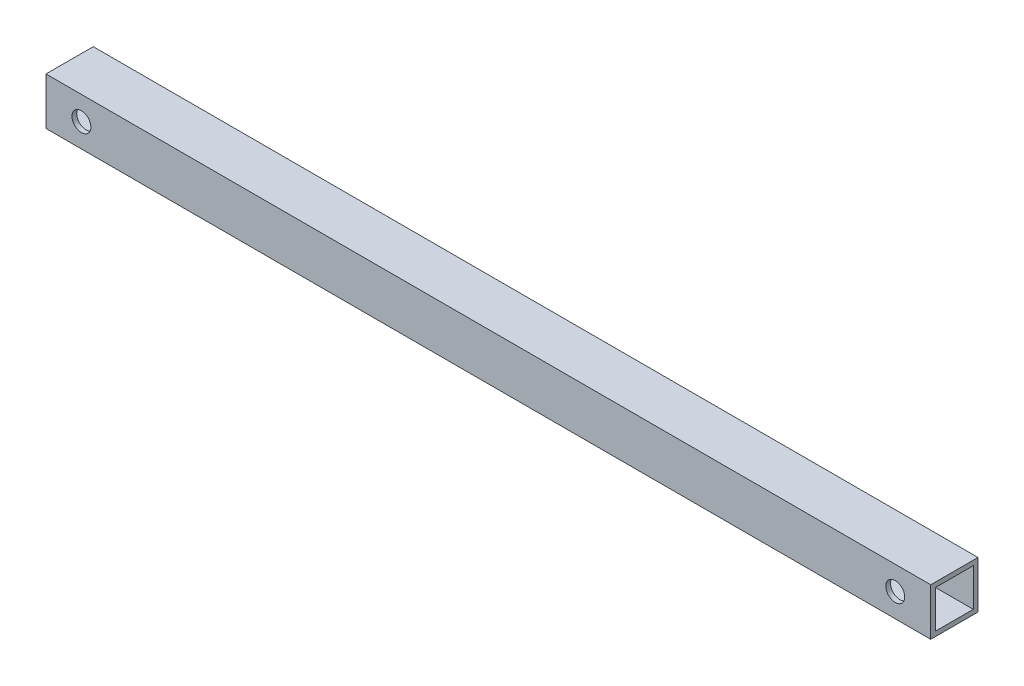
SolidWorks part; units mm, degrees
material "1060 合金"
ref_plane "正面" through (0, 0, 0) normal (0, 0, 1) x (1, 0, 0)
ref_plane "平面" through (0, 0, 0) normal (0, 1, 0) x (1, 0, 0)
ref_plane "右側面" through (0, 0, 0) normal (1, 0, 0) x (0, 0, -1)
sketch "ｽｹｯﾁ1" plane through (0, 0, 0) normal (1, 0, 0) x (0, 0, -1)
  line L1 (-5, -5) -> (5, -5)
  line L2 (-5, -5) -> (-5, 5)
  line L3 (-5, 5) -> (5, 5)
  line L4 (5, -5) -> (5, 5)
  line L5 (-5, -5) -> (5, 5) construction
  line L6 (-5, 5) -> (5, -5) construction
  point P0 (0, 0)
  dimension "D1" = 10
extrude "押し出し-薄板1" add sketch "ｽｹｯﾁ1" along normal blind 187.2 thin thin type one direction reverse wall 1
sketch "ｽｹｯﾁ2" plane through (0, 0, 5) normal (0, 0, 1) x (1, 0, 0)
  line L0 (0, 0) -> (-50000, 0) construction
  line L1 (0, 5) -> (0, -5) construction
  line L2 (93.6, 5) -> (93.6, -5) construction
  line L3 (187.2, 5) -> (0, 5) construction
  line L4 (187.2, -5) -> (0, -5) construction
  circle A0 centre (7.5, 0) radius 2
  circle A1 centre (179.7, 0) radius 2
  point P4 (0, 0)
  dimension "D1" = 7.5
  dimension "D2" = 4
extrude "ｶｯﾄ - 押し出し1" cut sketch "ｽｹｯﾁ2" against normal through all
